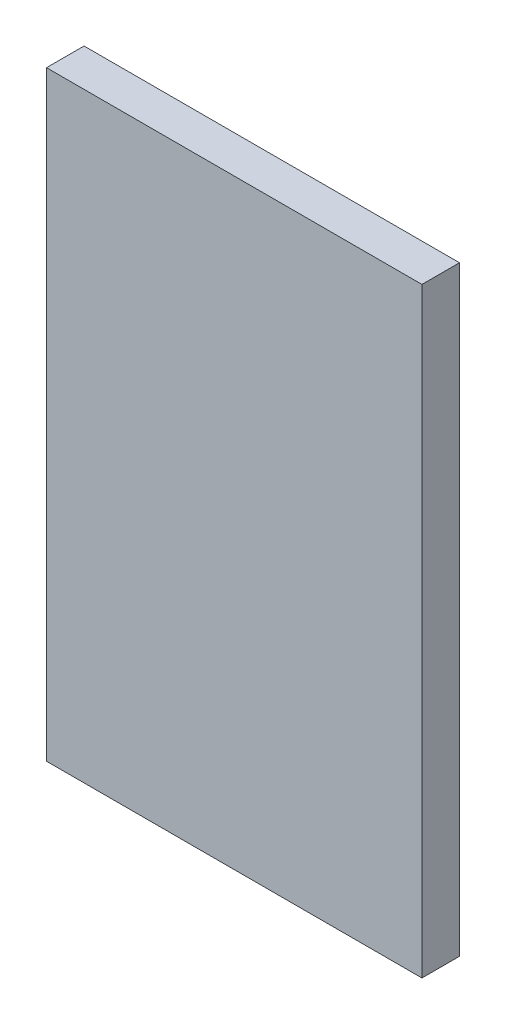
SolidWorks part; units mm, degrees
ref_plane "Front Plane" through (0, 0, 0) normal (0, 0, 1) x (1, 0, 0)
ref_plane "Top Plane" through (0, 0, 0) normal (0, 1, 0) x (1, 0, 0)
ref_plane "Right Plane" through (0, 0, 0) normal (1, 0, 0) x (0, 0, -1)
sketch "Sketch1" plane through (0, 0, 0) normal (0, 1, 0) x (1, 0, 0)
  line L1 (-15.875, -1.5875) -> (15.875, -1.5875)
  line L2 (-15.875, -1.5875) -> (-15.875, 1.5875)
  line L3 (-15.875, 1.5875) -> (15.875, 1.5875)
  line L4 (15.875, -1.5875) -> (15.875, 1.5875)
  line L5 (-15.875, -1.5875) -> (15.875, 1.5875) construction
  line L6 (-15.875, 1.5875) -> (15.875, -1.5875) construction
  point P0 (0, 0)
  dimension "D1" = 31.75
  dimension "D2" = 3.175
extrude "Boss-Extrude1" add sketch "Sketch1" along normal blind 50.8
